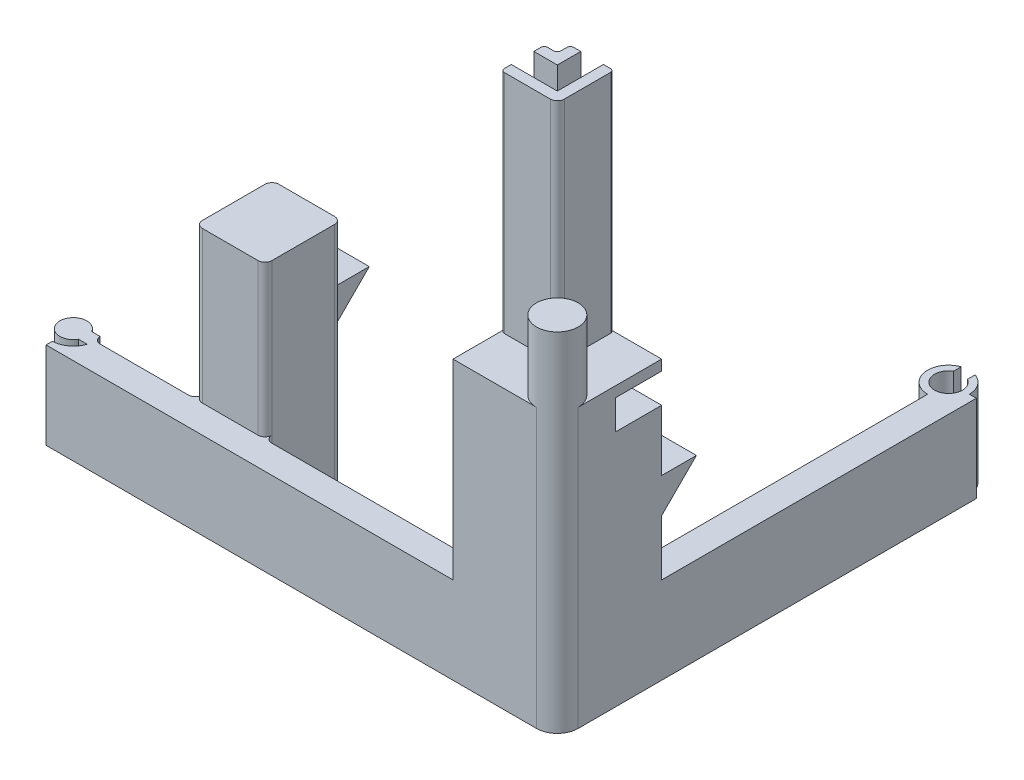
SolidWorks part; units mm, degrees
ref_plane "Front Plane" through (0, 0, 0) normal (0, 0, 1) x (1, 0, 0)
ref_plane "Top Plane" through (0, 0, 0) normal (0, 1, 0) x (1, 0, 0)
ref_plane "Right Plane" through (0, 0, 0) normal (1, 0, 0) x (0, 0, -1)
sketch "Sketch1" plane through (0, 0, 0) normal (0, 1, 0) x (1, 0, 0)
  line L1 (-15, -15) -> (15, -15)
  line L2 (-15, -15) -> (-15, 15)
  line L3 (-15, 15) -> (15, 15)
  line L4 (15, -15) -> (15, 15)
  line L5 (-15, -15) -> (15, 15) construction
  line L6 (-15, 15) -> (15, -15) construction
  point P0 (0, 0)
  dimension "D1" = 30
extrude "Boss-Extrude1" add sketch "Sketch1" along normal blind 80
sketch "Sketch2" plane through (0, 80, 0) normal (0, 1, 0) x (1, 0, 0)
  line L0 (-15, -15) -> (15, -15) construction
  line L1 (15, -15) -> (15, 15) construction
  circle A0 centre (9, -9) radius 6
  dimension "D1" = 12
extrude "Boss-Extrude2" add sketch "Sketch2" along normal blind 20
sketch "Sketch3" plane through (0, 80, 0) normal (0, 1, 0) x (1, 0, 0)
  line L2 (9, -15) -> (15, -15)
  line L4 (15, -15) -> (15, -9)
  circle A1 centre (9, -9) radius 6
  arc A4 (9, -15) -> (15, -9) centre (9, -9) ccw
  dimension "D1" = 0
extrude "Cut-Extrude1" cut sketch "Sketch3" against normal through all
sketch "Sketch4" plane through (0, 80, 0) normal (0, 1, 0) x (1, 0, 0)
  line L0 (1.25, 11.25) -> (1.25, 15)
  line L1 (-8.25, 11.25) -> (-1.75, 11.25) construction
  line L2 (-8.25, 11.25) -> (-8.25, 8.25)
  line L5 (1.25, 15) -> (-1.75, 15)
  line L6 (-1.75, 1.75) -> (-11.25, 1.75)
  line L8 (-8.25, 8.25) -> (-11.25, 8.25)
  line L9 (-11.25, 1.75) -> (-11.25, 8.25) construction
  line L10 (-1.75, 11.25) -> (-1.75, 1.75)
  line L11 (-11.25, -1.25) -> (1.25, -1.25)
  line L12 (1.25, -1.25) -> (1.25, 11.25)
  line L13 (1.25, 11.25) -> (-1.75, 11.25) construction
  line L14 (-11.25, 1.75) -> (-11.25, -1.25) construction
  line L15 (-11.25, 8.25) -> (-11.25, 11.25) construction
  line L16 (-11.25, 11.25) -> (-11.25, 15)
  line L17 (15, 15) -> (-15, 15) construction
  line L18 (-11.25, 11.25) -> (-8.25, 11.25) construction
  line L19 (-11.25, 15) -> (-8.25, 15)
  line L20 (-8.25, 15) -> (-8.25, 11.25)
  line L21 (-11.25, 8.25) -> (-15, 8.25)
  line L22 (-15, 15) -> (-15, -15) construction
  line L23 (-15, 8.25) -> (-15, 11.25)
  line L24 (-15, 11.25) -> (-11.25, 11.25)
  line L25 (-1.75, 15) -> (-1.75, 11.25)
  line L26 (-11.25, 1.75) -> (-15, 1.75)
  line L27 (-15, 1.75) -> (-15, -1.25)
  line L28 (-15, -1.25) -> (-11.25, -1.25)
  dimension "D1" = 6.5
  dimension "D3" = 3
  dimension "D4" = 3.75
extrude "Boss-Extrude3" add sketch "Sketch4" along normal blind 65
sketch "Sketch6" plane through (0, 0, 0) normal (0, -1, 0) x (1, 0, 0)
  line L1 (15, -15) -> (7, -15)
  line L2 (15, -15) -> (15, -105.5)
  line L3 (15, -105.5) -> (13, -105.5)
  line L4 (7, -15) -> (7, -99.5)
  arc A1 (7, -99.5) -> (13, -105.5) centre (7, -105.5) ccw
  dimension "D3" = 12
  dimension "D1" = 90.5
  dimension "D2" = 8
extrude "Boss-Extrude5" add sketch "Sketch6" against normal blind 2
sketch "Sketch7" plane through (0, 2, 0) normal (0, 1, 0) x (1, 0, 0)
  line L0 (7, 109.5) -> (7, 111.5) construction
  line L1 (9, 111.1569) -> (9, 108.9641)
  line L2 (5, 111.1569) -> (5, 108.9641)
  line L3 (7, 101.5) -> (7, 99.5) construction
  line L4 (15, 105.5) -> (13, 105.5)
  line L5 (15, 105.5) -> (15, 15)
  line L6 (15, 15) -> (7, 15)
  line L7 (7, 15) -> (7, 99.5) construction
  line L8 (15, 15) -> (1.25, 15) construction
  line L9 (7, 15) -> (7, 99.5)
  arc A0 (5, 111.1569) -> (7, 99.5) centre (7, 105.5) ccw
  arc A1 (13, 105.5) -> (7, 99.5) centre (7, 105.5) ccw construction
  arc A2 (5, 108.9641) -> (9, 108.9641) centre (7, 105.5) ccw
  arc A3 (13, 105.5) -> (9, 111.1569) centre (7, 105.5) ccw
  dimension "D1" = 2
  dimension "D2" = 2
extrude "Boss-Extrude6" add sketch "Sketch7" along normal offset from surface (23 mm away) 25 up to face at (3.75, 0, -38.4375)
sketch "Sketch9" plane through (0, 0, 0) normal (0, -1, 0) x (1, 0, 0)
  line L0 (15, -15) -> (7, -15) construction
  line L1 (-15, 15) -> (-132.175, 15) construction
  line L2 (-15, 15) -> (-15, 7)
  line L3 (-15, 7) -> (-126.175, 7) construction
  line L4 (-132.175, 15) -> (-132.175, 13.1746) construction
  line L5 (-136.05, 7) -> (-136.175, 7) construction
  line L6 (-128.175, 7) -> (-126.175, 7) construction
  line L7 (-126.175, 9) -> (-128.856, 9) construction
  line L8 (7, -109.5) -> (7, -111.5) construction
  line L9 (9, -111.1569) -> (5, -111.1569) construction
  line L10 (-126.175, 5) -> (-128.856, 5) construction
  line L11 (-126.175, 9) -> (-126.175, 5) construction
  line L12 (-128.7978, 8.9) -> (-126.3, 8.9)
  line L13 (-128.7978, 5.1) -> (-126.175, 5.1) construction
  line L14 (-126.175, 5.1) -> (-126.175, 7) construction
  line L15 (-126.175, 8.9) -> (-126.3, 8.9) construction
  line L16 (-132.05, 15) -> (-132.05, 13.1733)
  line L17 (-132.05, 14.0867) -> (-132.175, 14.0873) construction
  line L18 (-132.05, 15) -> (-15, 15)
  line L19 (-126.175, 5.1) -> (-126.175, 7) construction
  line L20 (-15, 7) -> (-126.175, 7)
  line L21 (-126.4838, 5.1) -> (-128.7978, 5.1)
  circle A0 centre (-132.175, 7) radius 4 construction
  arc A1 (9, -108.9641) -> (5, -108.9641) centre (7, -105.5) ccw construction
  arc A2 (-128.7978, 8.9) -> (-128.7978, 5.1) centre (-132.175, 7) ccw
  arc A4 (-126.3, 8.9) -> (-132.175, 13.1746) centre (-132.175, 7) ccw construction
  arc A6 (-126.3, 8.9) -> (-132.05, 13.1733) centre (-132.175, 7) ccw
  arc A7 (-126.4838, 5.1) -> (-126.175, 7) centre (-132.175, 7) ccw
  arc A8 (7, -99.5) -> (5, -111.1569) centre (7, -105.5) ccw construction
  dimension "D1" = 117.175
  dimension "D2" = 0.125
  dimension "D3" = 1.9
extrude "Boss-Extrude7" add sketch "Sketch9" against normal blind 25
fillet "Fillet1" radius 2 1 edges at (-126.175, 12.5, 7)
sketch "Sketch11" plane through (0, 0, 0) normal (0, -1, 0) x (1, 0, 0)
  line L0 (-126.3, 8.9) -> (-126.425, 8.9) construction
  line L2 (-126.3, 8.9) -> (-128.7978, 8.9) construction
  line L3 (-136.05, 7) -> (-136.175, 7) construction
  circle A0 centre (-132.175, 7) radius 6.0558
  arc A5 (-128.7978, 8.9) -> (-128.7978, 5.1) centre (-132.175, 7) ccw construction
extrude "Cut-Extrude2" cut sketch "Sketch11" against normal offset from surface (2.125 mm away) 0.125 up to face at (7, 2, -108.2802) offset beyond the face yes
sketch "Sketch12" plane through (15, 0, 0) normal (1, 0, 0) x (0, 0, -1)
  line L0 (15, 80) -> (15, 25) construction
  line L1 (15, 77) -> (1.75, 77)
  line L2 (15, 77) -> (15, 68.5)
  line L3 (15, 68.5) -> (1.75, 68.5)
  line L4 (1.75, 77) -> (1.75, 68.5)
  line L7 (-9, 80) -> (15, 80) construction
  line L9 (1.75, 145) -> (1.75, 80) construction
  dimension "D1" = 3
  dimension "D2" = 8.5
extrude "Cut-Extrude3" cut sketch "Sketch12" against normal through all both
sketch "Sketch13" plane through (0, 0, 15) normal (0, 0, 1) x (1, 0, 0)
  line L0 (15, 0) -> (-136.05, 0) construction
  line L1 (-136.05, 25) -> (-136.05, 2.125) construction
  line L2 (-132.05, 0) -> (9, 0) construction
fillet "Fillet2" radius 2 1 edges at (1.25, 112.5, 1.25)
sketch "Sketch15" plane through (0, 80, 0) normal (0, 1, 0) x (1, 0, 0)
  line L4 (-11.25, 11.25) -> (-11.25, 15)
  line L5 (-11.25, 15) -> (-15, 15)
  line L6 (-15, 15) -> (-15, 11.25)
  line L7 (-15, 11.25) -> (-11.25, 11.25)
  line L8 (-11.25, 11.25) -> (-11.25, 15)
  line L9 (-11.25, 15) -> (-15, 15)
  line L10 (-15, 15) -> (-15, 11.25)
  line L11 (-15, 11.25) -> (-11.25, 11.25)
  dimension "D1" = 0
extrude "Cut-Extrude4" cut sketch "Sketch15" against normal up to next
fillet "Fillet3" radius 1 5 edges at (-15, 112.5, 1.25) (1.25, 112.5, -15) (-11.25, 111, -15) (-11.25, 111, -11.25) (-15, 111, -11.25)
sketch "Sketch16" plane through (0, 0, 0) normal (0, -1, 0) x (1, 0, 0)
  line L0 (-124.429, 7) -> (-15, 7) construction
  line L1 (-77.0718, 7) -> (-97.0718, 7)
  line L2 (-77.0718, 7) -> (-77.0718, -15)
  line L3 (-77.0718, -15) -> (-97.0718, -15)
  line L4 (-97.0718, 7) -> (-97.0718, -15)
  line L5 (-69.7145, -7) -> (-69.7145, 15) construction
  line L6 (15, 15) -> (-136.05, 15) construction
  line L7 (-15, -15) -> (15, -15) construction
  line L8 (-124.429, 7) -> (-69.7145, 7) construction
  point P10 (-69.7145, 7)
  point P13 (-97.0718, 7)
  dimension "D1" = 20
extrude "Boss-Extrude8" add sketch "Sketch16" against normal up to surface (68.5 mm away) up to face at (0, 68.5, -8.375)
sketch "Sketch17" plane through (0, 0, 0) normal (0, -1, 0) x (1, 0, 0)
  line L0 (-97.0718, 7) -> (-77.0718, 7) construction
  line L1 (-94.5718, -12.5) -> (-79.5718, -12.5)
  line L2 (-94.5718, -12.5) -> (-94.5718, 4.5)
  line L3 (-94.5718, 4.5) -> (-79.5718, 4.5)
  line L4 (-79.5718, -12.5) -> (-79.5718, 4.5)
  line L5 (-77.0718, 7) -> (-77.0718, -15) construction
  line L6 (-77.0718, -15) -> (-97.0718, -15) construction
  line L7 (-97.0718, -15) -> (-97.0718, 7) construction
  line L8 (-94.5718, 4.5) -> (-94.5718, 7) construction
  line L10 (-97.0718, 4.5) -> (-94.5718, 4.5) construction
  line L11 (-79.5718, 4.5) -> (-77.0718, 4.5) construction
  line L12 (-94.5718, -15) -> (-94.5718, -12.5) construction
  dimension "D1" = 2.5
fillet "Fillet4" radius 2 4 edges at (-77.0718, 12.5, 7) (-97.0718, 12.5, 7) (-77.0718, 34.25, -15) (-97.0718, 34.25, -15)
fillet "Fillet5" radius 2 2 edges at (-77.0718, 46.75, 7) (-97.0718, 46.75, 7)
extrude "Cut-Extrude5" cut sketch "Sketch17" against normal offset from surface (66 mm away) 2.5 up to face at (-87.0718, 68.5, -4)
chamfer "Chamfer1" distance 7 angle 45 4 edges at (-87.0718, 66, 4.5) (-79.5718, 66, -4) (-87.0718, 66, -12.5) (-94.5718, 66, -4)
sketch "Sketch18" plane through (15, 0, 0) normal (1, 0, 0) x (0, 0, -1)
  line L0 (15, 68.5) -> (15, 51) construction
  line L1 (15, 68.5) -> (15, 25) construction
  line L2 (15, 51) -> (15, 41)
  line L3 (15, 41) -> (25, 51)
  line L4 (25, 51) -> (15, 51)
  dimension "D1" = 17.5
  dimension "D2" = 10
extrude "Boss-Extrude9" add sketch "Sketch18" against normal up to surface (30 mm away) up to face at (-15, 77.5625, -1.8438)
ref_plane "Plane1" through (-87.0718, 0, 0) normal (-1, 0, 0) x (0, 0, 1)
sketch "Sketch19" plane through (-87.0718, 0, 0) normal (-1, 0, 0) x (0, 0, 1)
  line L3 (-15, 41) -> (-15, 51)
  line L4 (-25, 51) -> (-15, 41)
  line L5 (-15, 51) -> (-25, 51)
  line L6 (-15, 41) -> (-15, 51)
  line L7 (-25, 51) -> (-15, 41)
  line L8 (-15, 51) -> (-25, 51)
  dimension "D1" = 0
extrude "Boss-Extrude10" add sketch "Sketch19" against normal up to vertex and the other way up to vertex
